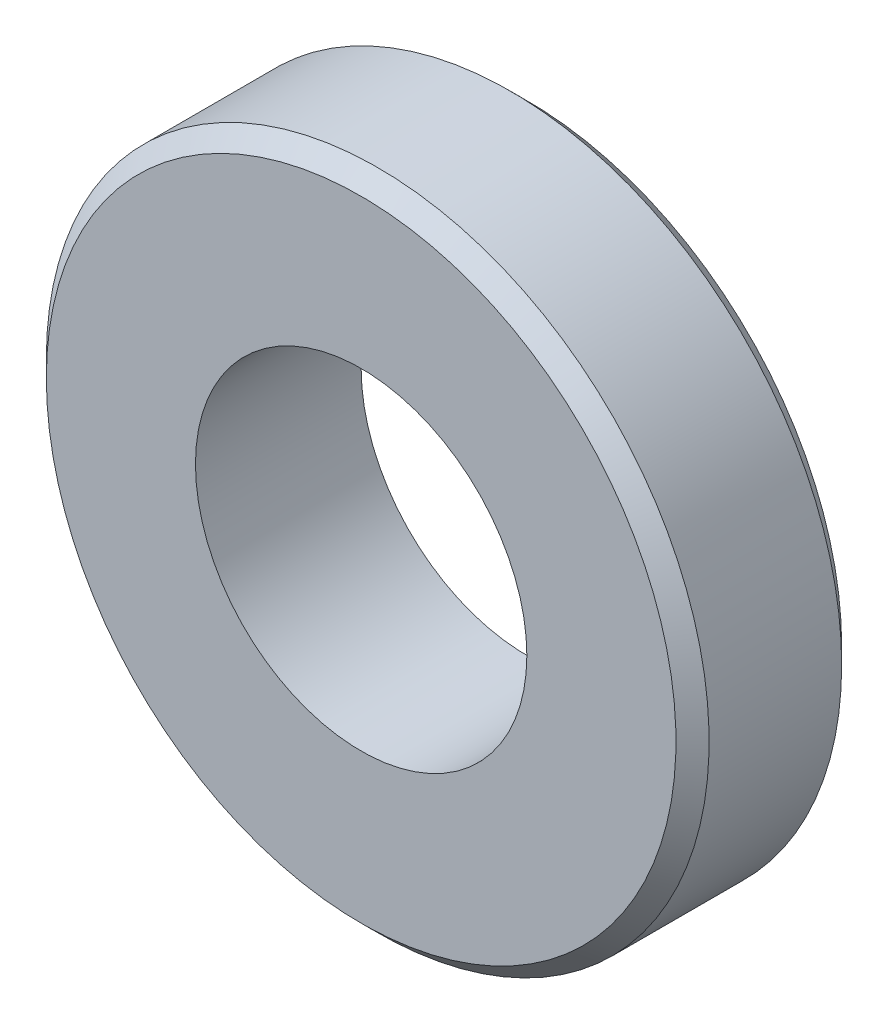
SolidWorks part; units mm, degrees
ref_plane "前视基准面" through (0, 0, 0) normal (0, 0, 1) x (1, 0, 0)
ref_plane "上视基准面" through (0, 0, 0) normal (0, 1, 0) x (1, 0, 0)
ref_plane "右视基准面" through (0, 0, 0) normal (1, 0, 0) x (0, 0, -1)
sketch "草图1" plane through (0, 0, 0) normal (0, 1, 0) x (1, 0, 0)
  line L0 (0, 0) -> (0, -1) construction
  line L1 (10, 5) -> (20, 5)
  line L2 (20, 5) -> (20, -5)
  line L3 (20, -5) -> (10, -5)
  line L4 (10, -5) -> (10, 5)
revolve "旋转1" add sketch "草图1" angle 360 about L0
chamfer "倒角1" distance 1 angle 45 2 edges at (-20, 0, -5) (-20, 0, 5)
